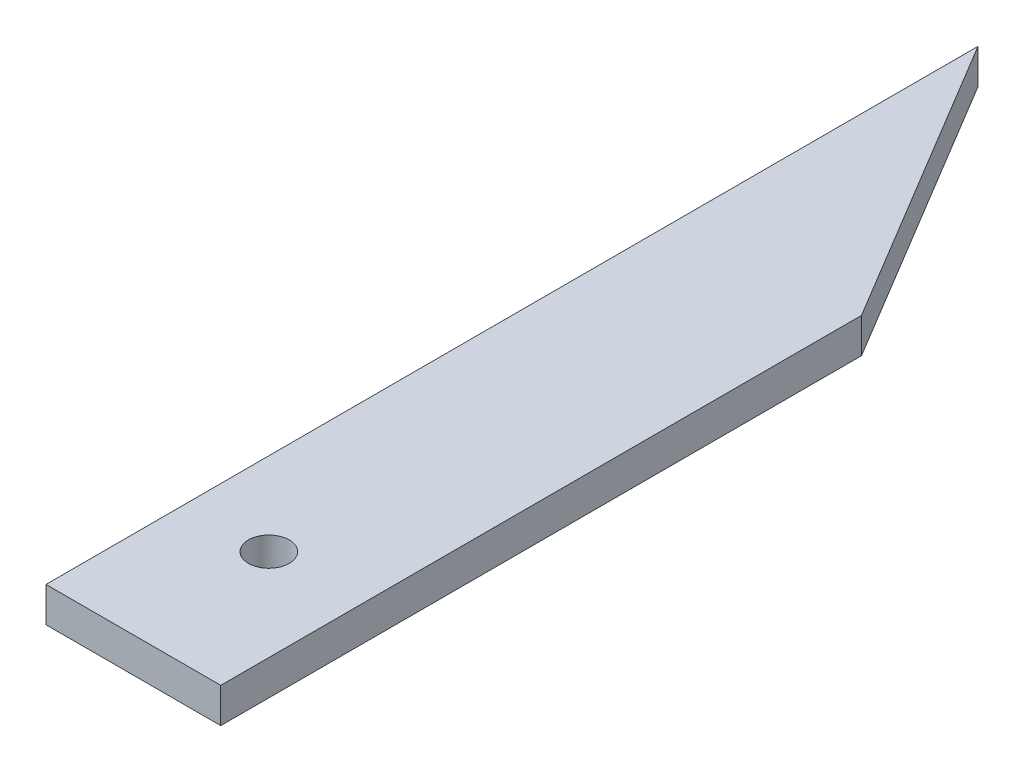
SolidWorks part; units mm, degrees
ref_plane "Front Plane" through (0, 0, 0) normal (0, 0, 1) x (1, 0, 0)
ref_plane "Top Plane" through (0, 0, 0) normal (0, 1, 0) x (1, 0, 0)
ref_plane "Right Plane" through (0, 0, 0) normal (1, 0, 0) x (0, 0, -1)
sketch "Sketch1" plane through (0, 0, 0) normal (0, 1, 0) x (1, 0, 0)
  line L0 (-7.1272, 38.0117) -> (7.8728, 13.0117)
  line L1 (-7.1272, -41.9883) -> (7.8728, -41.9883)
  line L2 (-7.1272, -41.9883) -> (-7.1272, 38.0117)
  line L4 (7.8728, -41.9883) -> (7.8728, 13.0117)
  line L5 (-7.1272, -41.9883) -> (3.4577, 20.3702) construction
  line L6 (-7.1272, 38.0117) -> (7.8728, -41.9883) construction
  circle A0 centre (0, -29.9883) radius 1.75
  point P0 (0, 0)
  dimension "D3" = 3.5
  dimension "D1" = 80
  dimension "D2" = 15
  dimension "D4" = 12
extrude "Boss-Extrude1" add sketch "Sketch1" along normal blind 3
